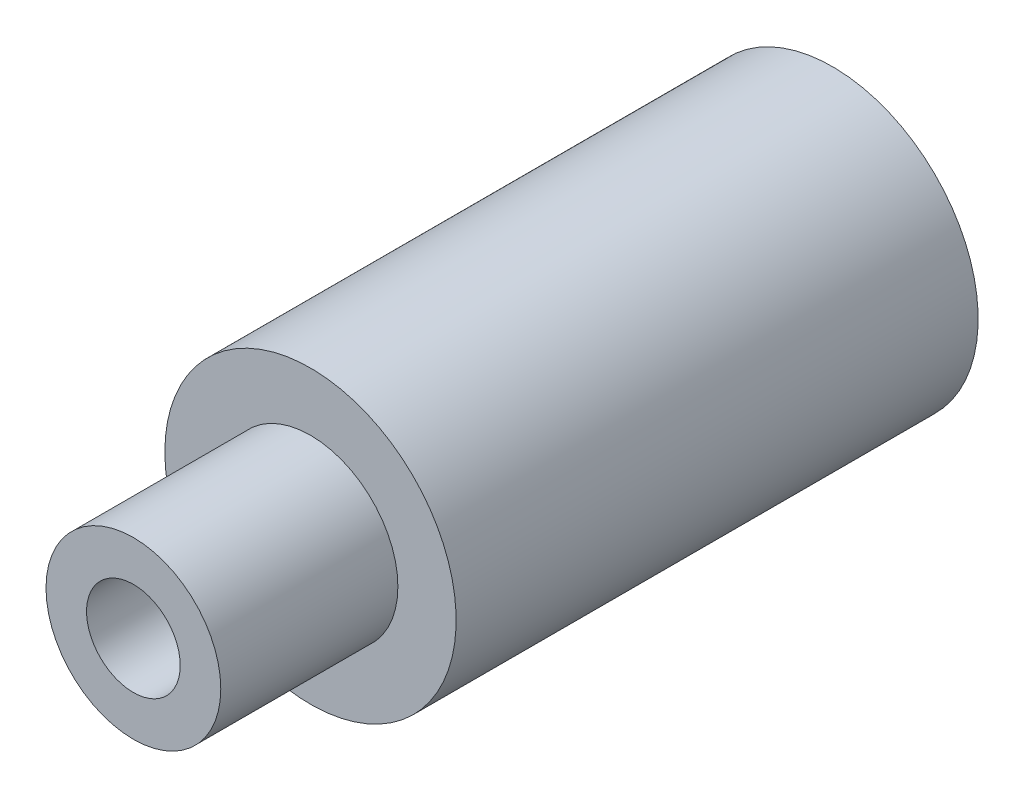
SolidWorks part; units mm, degrees
ref_plane "Front Plane" through (0, 0, 0) normal (0, 0, 1) x (1, 0, 0)
ref_plane "Top Plane" through (0, 0, 0) normal (0, 1, 0) x (1, 0, 0)
ref_plane "Right Plane" through (0, 0, 0) normal (1, 0, 0) x (0, 0, -1)
sketch "Sketch2" plane through (0, 0, 0) normal (0, 0, 1) x (1, 0, 0)
  circle A0 centre (0, 0) radius 7.9375
  dimension "D1" = 15.875
extrude "Cylinder Base" add sketch "Sketch2" along normal blind 38.1
sketch "Sketch3" plane through (0, 0, 38.1) normal (0, 0, 1) x (1, 0, 0)
  circle A0 centre (0, 0) radius 4.7625
  dimension "D1" = 9.525
extrude "Trim 1" cut sketch "Sketch3" against normal blind 9.652 and the other way through all flip side to cut
hole_wizard "1/4-20 Tapped Hole1" positions "Sketch6" profile "Sketch7" tap size "1/4-20" standard "ANSI Inch"
sketch "Sketch6" plane through (0, 0, 38.1) normal (0, 0, 1) x (1, 0, 0)
  point P0 (0, 0)
  point P3 (0, 0)
sketch "Sketch7" plane through (0, 0, 38.1) normal (1, 0, 0) x (0, -1, 0)
  line L0 (0, 0) -> (0, 19.05)
  line L1 (0, 19.05) -> (2.5527, 17.5162)
  line L2 (2.5527, 17.5162) -> (2.5527, 0)
  line L5 (2.5527, 0) -> (0, 0)
  line L10 (0, 19.05) -> (-2.5527, 17.5162) construction
  line L11 (0, -6.35) -> (0, 107.95) construction
  dimension "Tap Drill Dia." = 5.1054
  dimension "Tap Drill Depth" = 19.05
  dimension "Drill Angle" = 118
cosmetic thread "Hole Thread2"
hole_wizard "1/4-20 Tapped Hole9" positions "Sketch18" profile "Sketch19" tap size "1/4-20" standard "ANSI Inch"
sketch "Sketch18" plane through (0, 0, 0) normal (0, 0, -1) x (-1, 0, 0)
  point P0 (0, 0)
sketch "Sketch19" plane through (0, 0, 0) normal (1, 0, 0) x (0, 1, 0)
  line L0 (0, 0) -> (0, 13.97)
  line L1 (0, 13.97) -> (2.5527, 12.4362)
  line L2 (2.5527, 12.4362) -> (2.5527, 0)
  line L5 (2.5527, 0) -> (0, 0)
  line L10 (0, 13.97) -> (-2.5527, 12.4362) construction
  line L11 (0, -6.35) -> (0, 107.95) construction
  dimension "Tap Drill Dia." = 5.1054
  dimension "Tap Drill Depth" = 13.97
  dimension "Drill Angle" = 118
cosmetic thread "Hole Thread3"
sketch "Sketch20" plane through (0, 0, 38.1) normal (0, 0, 1) x (1, 0, 0)
  circle A0 centre (0, 0) radius 2.5527
  dimension "D1" = 5.1054
extrude "Cut-Extrude2" cut sketch "Sketch20" against normal through all
